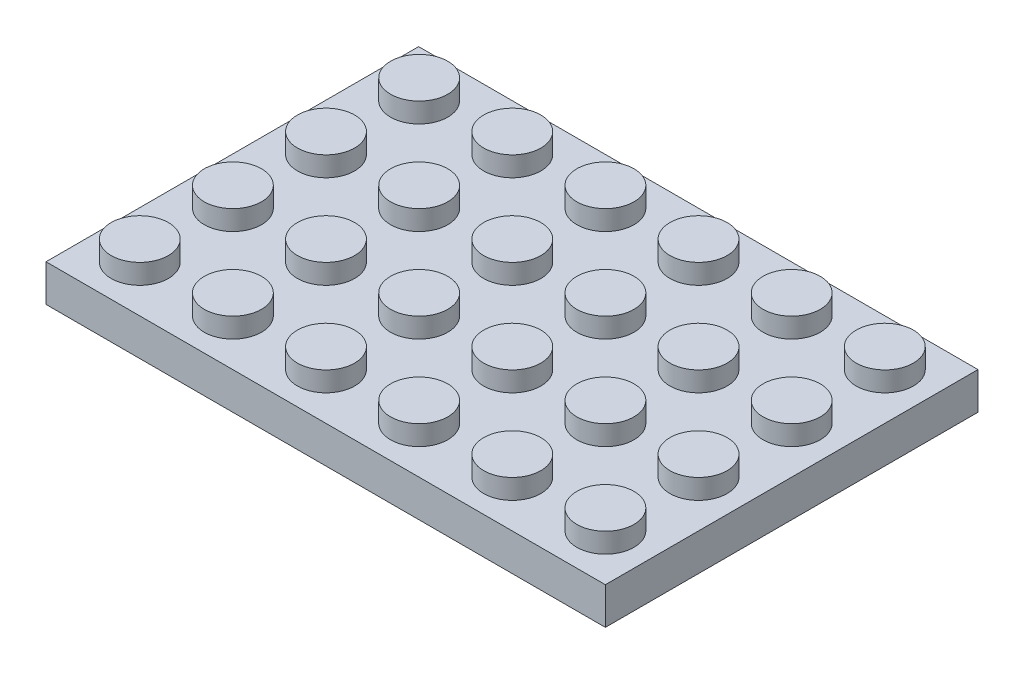
SolidWorks part; units mm, degrees
ref_plane "Front Plane" through (0, 0, 0) normal (0, 0, 1) x (1, 0, 0)
ref_plane "Top Plane" through (0, 0, 0) normal (0, 1, 0) x (1, 0, 0)
ref_plane "Right Plane" through (0, 0, 0) normal (1, 0, 0) x (0, 0, -1)
sketch "Sketch1" plane through (0, 0, 0) normal (0, 1, 0) x (1, 0, 0)
  line L1 (-23.905, 15.925) -> (23.905, 15.925)
  line L2 (-23.905, 15.925) -> (-23.905, -15.925)
  line L3 (-23.905, -15.925) -> (23.905, -15.925)
  line L4 (23.905, 15.925) -> (23.905, -15.925)
  line L5 (-23.905, 15.925) -> (23.905, -15.925) construction
  line L6 (-23.905, -15.925) -> (23.905, 15.925) construction
  point P0 (0, 0)
  dimension "D1" = 31.85
  dimension "D2" = 47.81
extrude "Boss-Extrude1" add sketch "Sketch1" against normal blind 3.16
sketch "Sketch2" plane through (0, 0, 0) normal (0, 1, 0) x (1, 0, 0)
  line L1 (23.905, -15.925) -> (23.905, 15.925) construction
  line L2 (23.905, 15.925) -> (-23.905, 15.925) construction
  circle A0 centre (19.9208, 11.9438) radius 2.445
  circle A1 centre (11.9608, 11.9438) radius 2.445
  circle A2 centre (4.0008, 11.9438) radius 2.445
  circle A3 centre (-3.9592, 11.9438) radius 2.445
  circle A4 centre (-11.9192, 11.9438) radius 2.445
  circle A5 centre (-19.8792, 11.9438) radius 2.445
  circle A6 centre (11.9608, 3.9838) radius 2.445
  circle A7 centre (4.0008, 3.9838) radius 2.445
  circle A8 centre (-3.9592, 3.9838) radius 2.445
  circle A9 centre (-11.9192, 3.9838) radius 2.445
  circle A10 centre (-19.8792, 3.9838) radius 2.445
  circle A11 centre (11.9608, -3.9762) radius 2.445
  circle A12 centre (4.0008, -3.9762) radius 2.445
  circle A13 centre (-3.9592, -3.9762) radius 2.445
  circle A14 centre (-11.9192, -3.9762) radius 2.445
  circle A15 centre (-19.8792, -3.9762) radius 2.445
  circle A16 centre (11.9608, -11.9362) radius 2.445
  circle A17 centre (4.0008, -11.9362) radius 2.445
  circle A18 centre (-3.9592, -11.9362) radius 2.445
  circle A19 centre (-11.9192, -11.9362) radius 2.445
  circle A20 centre (-19.8792, -11.9362) radius 2.445
  circle A21 centre (19.9208, 3.9838) radius 2.445
  circle A22 centre (19.9208, -3.9762) radius 2.445
  circle A23 centre (19.9208, -11.9362) radius 2.445
  dimension "D1" = 4.89
  dimension "D2" = 3.9842
  dimension "D6" = 7.96
  dimension "D7" = 3.9842
  dimension "D3" = 3.9813
  dimension "D4" = 6
  dimension "D5" = 4
extrude "Boss-Extrude2" add sketch "Sketch2" along normal blind 1.7
shell "Shell1" thickness 0.78
sketch "Sketch3" plane through (0, -0.78, 0) normal (0, -1, 0) x (1, 0, 0)
  line L0 (-23.905, -15.925) -> (-23.905, 15.925) construction
  line L2 (-23.905, 15.925) -> (23.905, 15.925) construction
  circle A0 centre (-15.9367, 7.9625) radius 2.35
  circle A1 centre (-15.9367, 7.9625) radius 2.175
  circle A2 centre (-7.9667, 7.9625) radius 2.35
  circle A3 centre (-7.9667, 7.9625) radius 2.175
  circle A4 centre (0.0033, 7.9625) radius 2.35
  circle A5 centre (0.0033, 7.9625) radius 2.175
  circle A6 centre (7.9733, 7.9625) radius 2.35
  circle A7 centre (7.9733, 7.9625) radius 2.175
  circle A8 centre (15.9433, 7.9625) radius 2.35
  circle A9 centre (15.9433, 7.9625) radius 2.175
  circle A10 centre (-7.9667, 0.0025) radius 2.35
  circle A11 centre (-7.9667, 0.0025) radius 2.175
  circle A12 centre (0.0033, 0.0025) radius 2.35
  circle A13 centre (0.0033, 0.0025) radius 2.175
  circle A14 centre (7.9733, 0.0025) radius 2.35
  circle A15 centre (7.9733, 0.0025) radius 2.175
  circle A16 centre (15.9433, 0.0025) radius 2.35
  circle A17 centre (15.9433, 0.0025) radius 2.175
  circle A18 centre (-7.9667, -7.9575) radius 2.35
  circle A19 centre (-7.9667, -7.9575) radius 2.175
  circle A20 centre (0.0033, -7.9575) radius 2.35
  circle A21 centre (0.0033, -7.9575) radius 2.175
  circle A22 centre (7.9733, -7.9575) radius 2.35
  circle A23 centre (7.9733, -7.9575) radius 2.175
  circle A24 centre (15.9433, -7.9575) radius 2.35
  circle A25 centre (15.9433, -7.9575) radius 2.175
  circle A26 centre (-15.9367, 0.0025) radius 2.35
  circle A27 centre (-15.9367, 0.0025) radius 2.175
  circle A28 centre (-15.9367, -7.9575) radius 2.35
  circle A29 centre (-15.9367, -7.9575) radius 2.175
  dimension "D1" = 4.35
  dimension "D2" = 4.7
  dimension "D3" = 7.9683
  dimension "D4" = 7.9625
  dimension "D7" = 7.96
  dimension "D8" = 7.97
  dimension "D9" = 7.9683
  dimension "D5" = 5
  dimension "D6" = 3
extrude "Boss-Extrude3" add sketch "Sketch3" along normal offset from surface (2.18 mm away) 0.2 up to face at (0, -3.16, 0)
